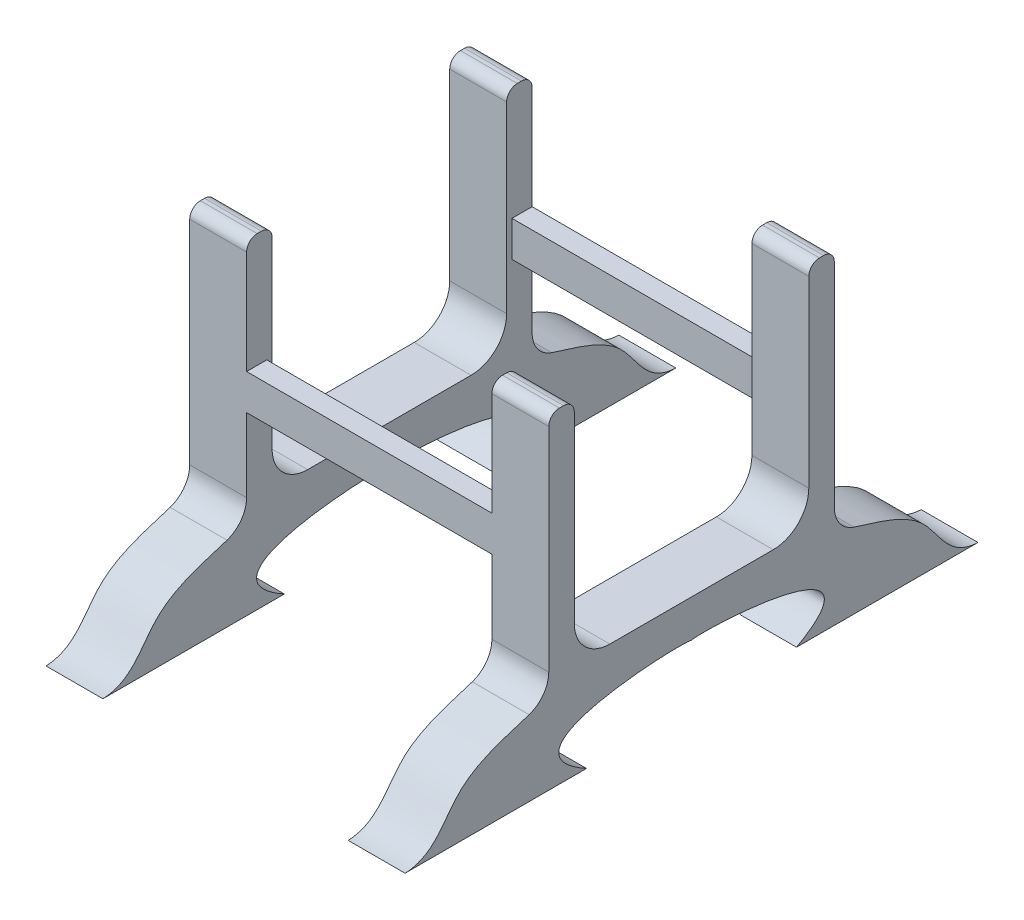
SolidWorks part; units mm, degrees
ref_plane "前视基准面" through (0, 0, 0) normal (0, 0, 1) x (1, 0, 0)
ref_plane "上视基准面" through (0, 0, 0) normal (0, 1, 0) x (1, 0, 0)
ref_plane "右视基准面" through (0, 0, 0) normal (1, 0, 0) x (0, 0, -1)
sketch "草图1" plane through (0, 0, 0) normal (1, 0, 0) x (0, 0, -1)
  line L0 (-91.224, 42.1042) -> (-90.0495, 42.1042)
  line L1 (-87.0495, 39.1042) -> (-87.0495, -12.4794)
  line L2 (-54.0648, -66.1426) -> (-54.0648, 77.6636) construction
  line L3 (-87.0495, -20.3263) -> (-87.0495, -22.4794)
  line L4 (-77.0495, -22.4794) -> (-31.08, -22.4794)
  line L5 (-94.224, 39.1042) -> (-94.224, -20.7163)
  line L7 (-124.9878, -49.5077) -> (27.0541, -49.5077) construction
  line L8 (-83.597, -49.5077) -> (-135.9023, -49.5077)
  line L9 (-24.5325, -49.5077) -> (27.7728, -49.5077)
  line L10 (-13.9055, 39.1042) -> (-13.9055, -20.7163)
  line L11 (-21.08, -20.3263) -> (-21.08, -22.4794)
  line L12 (-21.08, 39.1042) -> (-21.08, -12.4794)
  line L13 (-16.9055, 42.1042) -> (-18.08, 42.1042)
  arc A0 (-77.0495, -22.4794) -> (-87.0495, -12.4794) centre (-77.0495, -12.4794) cw
  arc A1 (-90.0495, 42.1042) -> (-87.0495, 39.1042) centre (-90.0495, 39.1042) cw
  arc A2 (-94.224, 39.1042) -> (-91.224, 42.1042) centre (-91.224, 39.1042) cw
  arc A3 (-99.7441, -28.3222) -> (-94.224, -20.7163) centre (-102.224, -20.7163) ccw
  arc A4 (-8.3855, -28.3222) -> (-13.9055, -20.7163) centre (-5.9055, -20.7163) cw
  arc A5 (-13.9055, 39.1042) -> (-16.9055, 42.1042) centre (-16.9055, 39.1042) ccw
  arc A6 (-18.08, 42.1042) -> (-21.08, 39.1042) centre (-18.08, 39.1042) ccw
  arc A7 (-31.08, -22.4794) -> (-21.08, -12.4794) centre (-31.08, -12.4794) ccw
  ellipse E0 centre (-53.3247, -49.5077) end of major axis (16.8583, -47.5861) minor radius 27.0385 (-54.0648, -22.4794) -> (-44.128, -22.4794) cw
  ellipse E2 centre (-54.8048, -49.5077) end of major axis (-124.9878, -47.5861) minor radius 27.0385 (-54.0648, -22.4794) -> (-64.0016, -22.4794) ccw
  spline S0 degree 3 poles (-54.0648, -33.0596) (-55.1134, -31.9572) (-111.6942, -33.8411) (-83.597, -49.5077) knots 0 0 0 0 1 1 1 1
  spline S1 degree 3 poles (-99.7441, -28.3222) (-104.134, -29.7536) (-111.1399, -31.5588) (-123.3743, -39.2828) (-126.3014, -49.8758) (-135.9023, -49.5077) knots 0.13005 0.13005 0.13005 0.13005 0.418291 0.563236 1 1 1 1
  spline S2 degree 3 poles (-8.3855, -28.3222) (-3.9955, -29.7536) (3.0103, -31.5588) (15.2448, -39.2828) (18.1719, -49.8758) (27.7728, -49.5077) knots 0.13005 0.13005 0.13005 0.13005 0.418291 0.563236 1 1 1 1
  spline S3 degree 3 poles (-54.0648, -33.0596) (-53.0162, -31.9572) (3.5646, -33.8411) (-24.5325, -49.5077) knots 0 0 0 0 1 1 1 1
  dimension "D2" = 10
  dimension "D3" = 3
  dimension "D1" = 8
extrude "凸台-拉伸1" add sketch "草图1" along normal blind 16
move or copy body "实体-移动/复制1" bodies to move or copy 101 copy yes number of copies 1 translate (85, 0, 0) parameters "D1"=85, "D2"=0, "D3"=0
sketch "草图2" plane through (0, 0, 0) normal (0, 1, 0) x (1, 0, 0)
  line L0 (16, -88.5495) -> (85, -88.5495)
  line L1 (16, -90.0495) -> (16, -87.0495) construction
  line L2 (85, -87.0495) -> (85, -90.0495) construction
  line L3 (85, -88.5495) -> (85, -94.224)
  line L4 (85, -91.224) -> (85, -94.224) construction
  line L5 (85, -94.224) -> (16, -94.224)
  line L6 (16, -94.224) -> (16, -88.5495)
  line L7 (-36.6506, -54.0648) -> (180.3248, -54.0648) construction
  line L8 (16, -13.9055) -> (16, -19.58)
  line L9 (85, -13.9055) -> (16, -13.9055)
  line L10 (85, -19.58) -> (85, -13.9055)
  line L11 (16, -19.58) -> (85, -19.58)
extrude "凸台-拉伸2" add sketch "草图2" along normal blind 10
